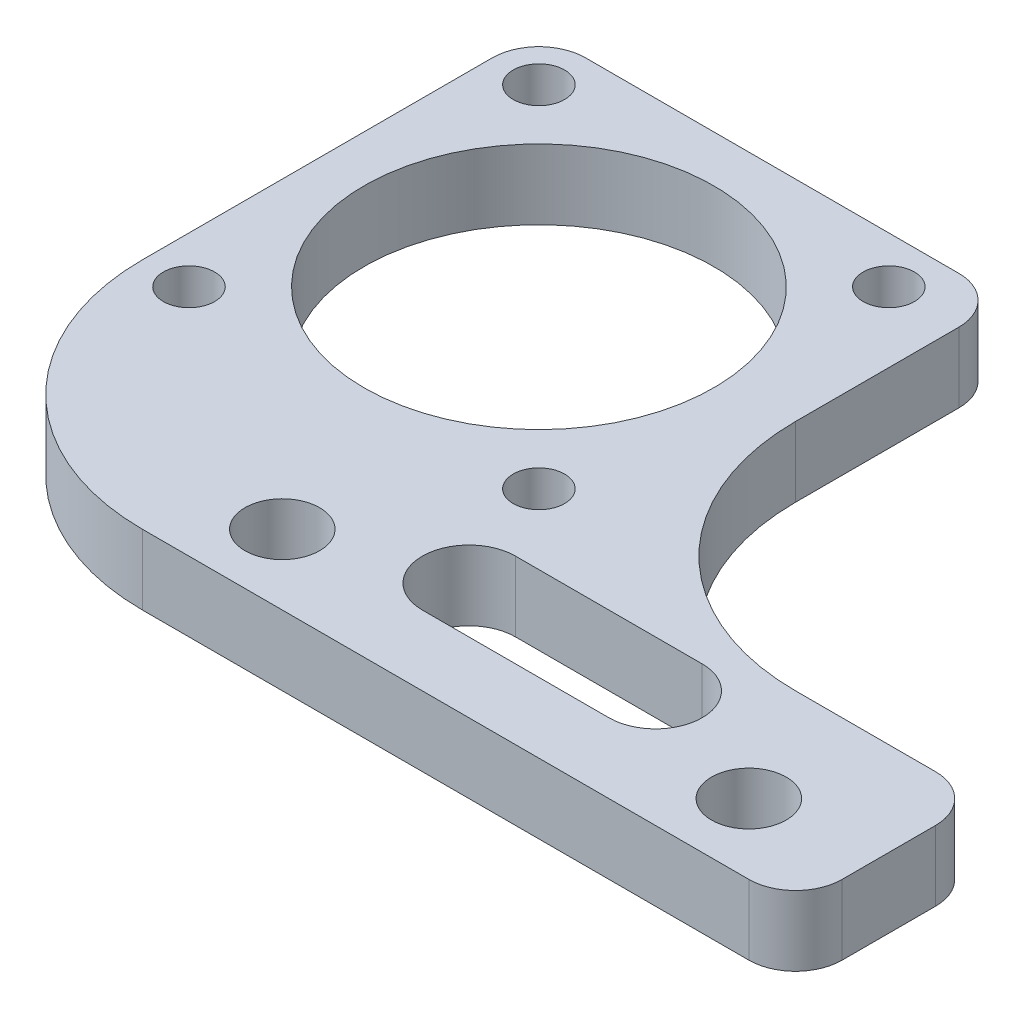
SolidWorks part; units mm, degrees
material "Thornel Mat VMA"
ref_plane "前视基准面" through (0, 0, 0) normal (0, 0, 1) x (1, 0, 0)
ref_plane "上视基准面" through (0, 0, 0) normal (0, 1, 0) x (1, 0, 0)
ref_plane "右视基准面" through (0, 0, 0) normal (1, 0, 0) x (0, 0, -1)
other "Configuration Table"
sketch "草图1" plane through (0, 0, 0) normal (0, 1, 0) x (1, 0, 0)
  line L0 (3.5, -14.5) -> (23.5, -14.5) construction
  line L1 (-7.5, 7.5) -> (7.5, 7.5) construction
  line L2 (-7.5, 7.5) -> (-7.5, -7.5) construction
  line L3 (-7.5, -7.5) -> (7.5, -7.5) construction
  line L4 (7.5, 7.5) -> (7.5, -7.5) construction
  line L5 (-7.5, 7.5) -> (7.5, -7.5) construction
  line L6 (-7.5, -7.5) -> (7.5, 7.5) construction
  line L7 (-9.5, 9.5) -> (28.5, 9.5)
  line L8 (-9.5, 9.5) -> (-9.5, -17.5)
  line L9 (-9.5, -17.5) -> (28.5, -17.5)
  line L10 (28.5, 9.5) -> (28.5, -17.5)
  circle A0 centre (7.5, -7.5) radius 1.1
  circle A1 centre (7.5, 7.5) radius 1.1
  circle A2 centre (-7.5, 7.5) radius 1.1
  circle A3 centre (-7.5, -7.5) radius 1.1
  circle A4 centre (3.5, -14.5) radius 1.6
  circle A5 centre (23.5, -14.5) radius 1.6
  point P0 (0, 0)
  dimension "D2" = 2.2
  dimension "D10" = 3.2
  dimension "D1" = 15
  dimension "D3" = 2
  dimension "D4" = 2
  dimension "D5" = 10
  dimension "D6" = 20
  dimension "D7" = 3
  dimension "D8" = 5
  dimension "D9" = 13
extrude "凸台-拉伸1" add sketch "草图1" along normal blind 3
sketch "草图2" plane through (0, 3, 0) normal (0, 1, 0) x (1, 0, 0)
  line L0 (28.5, 9.5) -> (-9.5, 9.5) construction
  line L1 (10.5, 9.5) -> (28.5, 9.5)
  line L2 (10.5, 9.5) -> (10.5, -9.5)
  line L3 (10.5, -9.5) -> (28.5, -9.5)
  line L4 (28.5, 9.5) -> (28.5, -9.5)
  line L5 (28.5, -17.5) -> (28.5, 9.5) construction
  line L6 (-9.5, -17.5) -> (28.5, -17.5) construction
  line L7 (9.5, -12.5) -> (17.5, -12.5) construction
  line L8 (9.5, -10.9) -> (17.5, -10.9) construction
  line L9 (9.5, -14.1) -> (17.5, -14.1) construction
  line L10 (9.5, -12.5) -> (9.5, -17.5) construction
  circle A0 centre (0, 0) radius 10.6066 construction
  circle A1 centre (7.5, -7.5) radius 1.1 construction
  circle A2 centre (7.5, -7.5) radius 1.1 construction
  circle A3 centre (0, 0) radius 7.5
  arc A4 (9.5, -10.9) -> (9.5, -14.1) centre (9.5, -12.5) ccw construction
  arc A5 (17.5, -14.1) -> (17.5, -10.9) centre (17.5, -12.5) ccw construction
  circle A6 centre (3.5, -14.5) radius 1.6 construction
  point P20 (13.5, -12.5)
  dimension "D1" = 15
  dimension "D6" = 6
  dimension "D2" = 8
  dimension "D3" = 3
  dimension "D4" = 8
  dimension "D5" = 5
extrude "切除-拉伸1" cut sketch "草图2" against normal blind 21.5
fillet "圆角1" radius 10 2 edges at (-9.5, 1.5, 17.5) (10.5, 1.5, 9.5)
sketch "草图3" plane through (0, 3, 0) normal (0, 1, 0) x (1, 0, 0)
  line L0 (9.5, -12.5) -> (17.5, -12.5) construction
  line L1 (9.5, -10.5) -> (17.5, -10.5)
  line L2 (9.5, -14.5) -> (17.5, -14.5)
  line L3 (9.5, -12.5) -> (9.5, -17.5) construction
  line L12 (0.5, -17.5) -> (28.5, -17.5) construction
  arc A0 (9.5, -10.5) -> (9.5, -14.5) centre (9.5, -12.5) ccw
  arc A1 (17.5, -14.5) -> (17.5, -10.5) centre (17.5, -12.5) ccw
  circle A3 centre (3.5, -14.5) radius 1.6 construction
  point P2 (13.5, -12.5)
  dimension "D2" = 2
  dimension "D1" = 8
  dimension "D3" = 6
  dimension "D4" = 5
extrude "切除-拉伸2" cut sketch "草图3" against normal blind 21.5
fillet "圆角2" radius 2 4 edges at (-9.5, 1.5, -9.5) (10.5, 1.5, -9.5) (28.5, 1.5, 9.5) (28.5, 1.5, 17.5)
